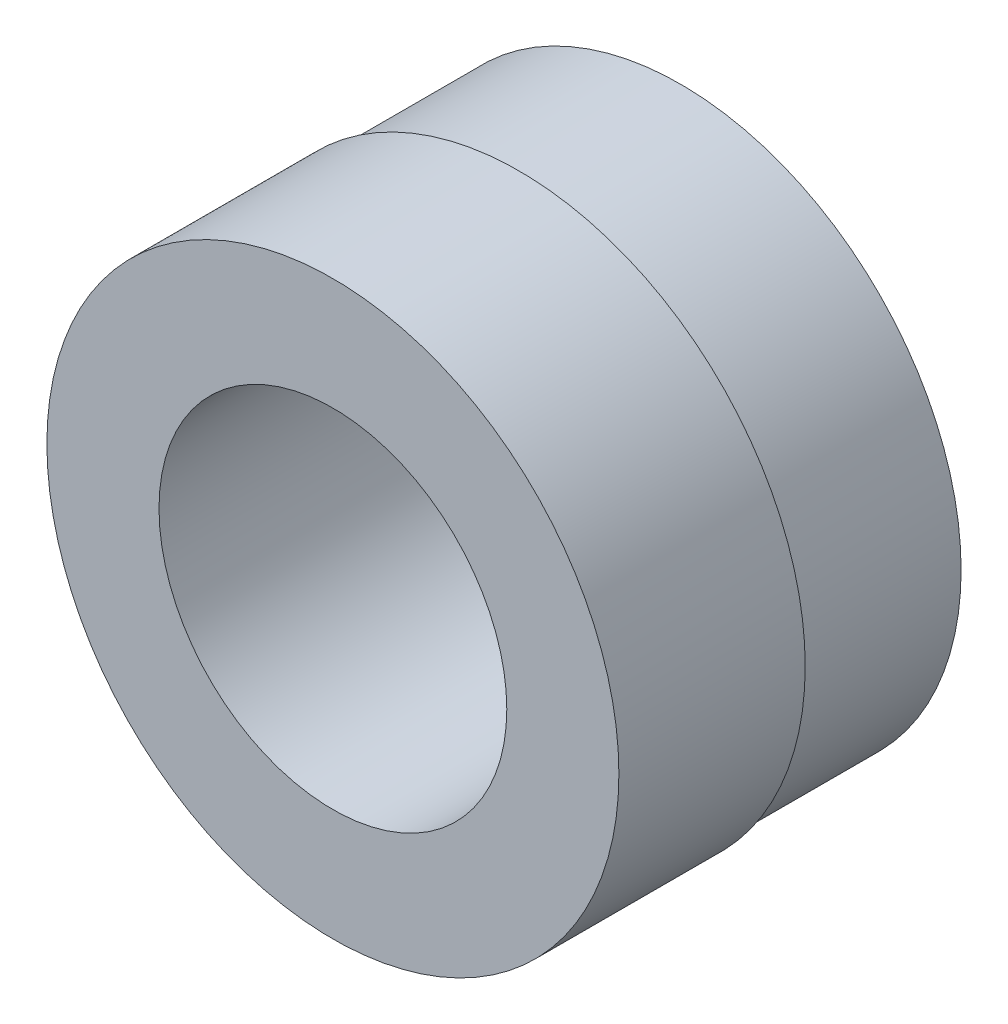
SolidWorks part; units mm, degrees
material "PET"
ref_plane "Front Plane" through (0, 0, 0) normal (0, 0, 1) x (1, 0, 0)
ref_plane "Top Plane" through (0, 0, 0) normal (0, 1, 0) x (1, 0, 0)
ref_plane "Right Plane" through (0, 0, 0) normal (1, 0, 0) x (0, 0, -1)
sketch "Sketch1" plane through (0, 0, 0) normal (0, 1, 0) x (1, 0, 0)
  line L0 (23.025, -13) -> (0, -13)
  line L1 (0, -13) -> (0, -28)
  line L2 (0, -28) -> (23.025, -28)
  line L3 (23.025, -28) -> (23.025, -13)
  line L4 (0, -13) -> (0, -28) construction
revolve "Revolve1" add sketch "Sketch1" angle 360 about L4
sketch "Sketch2" plane through (0, 0, 13) normal (0, 0, -1) x (-1, 0, 0)
  circle A0 centre (0, 0) radius 22.575
extrude "Boss-Extrude1" add sketch "Sketch2" along normal blind 13
hole_wizard "Hole1" positions "Sketch4" profile "Sketch3" legacy
sketch "Sketch4" plane through (0, 0, 28) normal (0, 0, 1) x (1, 0, 0)
  point P0 (0, 0)
sketch "Sketch3" plane through (0, 0, 28) normal (1, 0, 0) x (0, -1, 0)
  line L0 (0, 0) -> (0, 28)
  line L1 (0, 28) -> (10, 28)
  line L2 (10, 28) -> (10, 27)
  line L3 (10, 27) -> (14, 27)
  line L4 (14, 27) -> (14, 0)
  line L5 (14, 0) -> (0, 0)
  line L6 (0, 110) -> (0, -10) construction
  dimension "Diameter" = 20
  dimension "Depth" = 28
  dimension "C-Bore Diameter" = 28
  dimension "C-Bore Depth" = 27
hole_wizard "M2 Clearance Hole1" positions "Sketch6" profile "Sketch5" hole size "M2" standard "ANSI Metric"
sketch "Sketch6" plane through (0, 0, 0) normal (0, 0, -1) x (-1, 0, 0)
  point P0 (0, 17.5)
  point P1 (-17.5, 0)
  point P2 (0, -17.5)
  point P3 (17.5, 0)
sketch "Sketch5" plane through (0, 17.5, 0) normal (1, 0, 0) x (0, 1, 0)
  line L0 (0, 0) -> (0, 15.7388)
  line L1 (0, 15.7388) -> (1.2295, 15)
  line L2 (1.2295, 15) -> (1.2295, 0)
  line L5 (1.2295, 0) -> (0, 0)
  line L10 (0, 15.7388) -> (-1.2295, 15) construction
  line L11 (0, -6.35) -> (0, 107.95) construction
  dimension "Hole Dia." = 2.459
  dimension "Hole Depth" = 15
  dimension "Drill Angle" = 118
